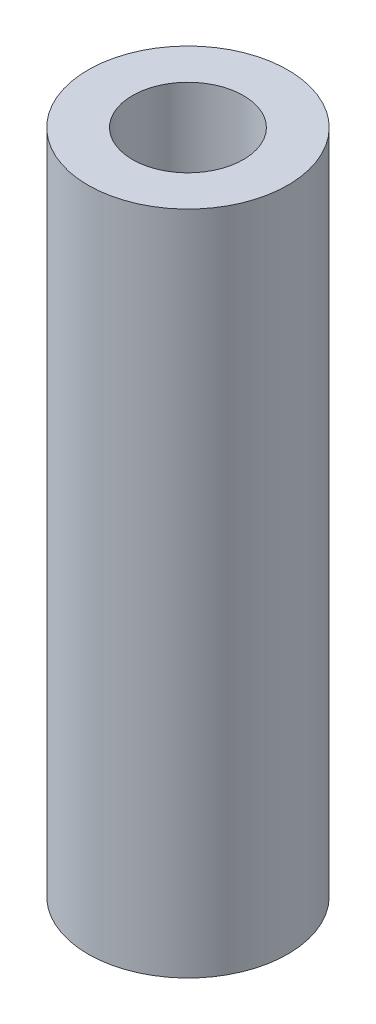
SolidWorks part; units mm, degrees
ref_plane "Front Plane" through (0, 0, 0) normal (0, 0, 1) x (1, 0, 0)
ref_plane "Top Plane" through (0, 0, 0) normal (0, 1, 0) x (1, 0, 0)
ref_plane "Right Plane" through (0, 0, 0) normal (1, 0, 0) x (0, 0, -1)
sketch "Sketch1" plane through (0, 0, 0) normal (0, 1, 0) x (1, 0, 0)
  circle A0 centre (0, 0) radius 1.25
  circle A1 centre (0, 0) radius 2.25
  dimension "D1" = 2.5
  dimension "D2" = 4.5
extrude "Boss-Extrude1" add sketch "Sketch1" along normal blind 15
